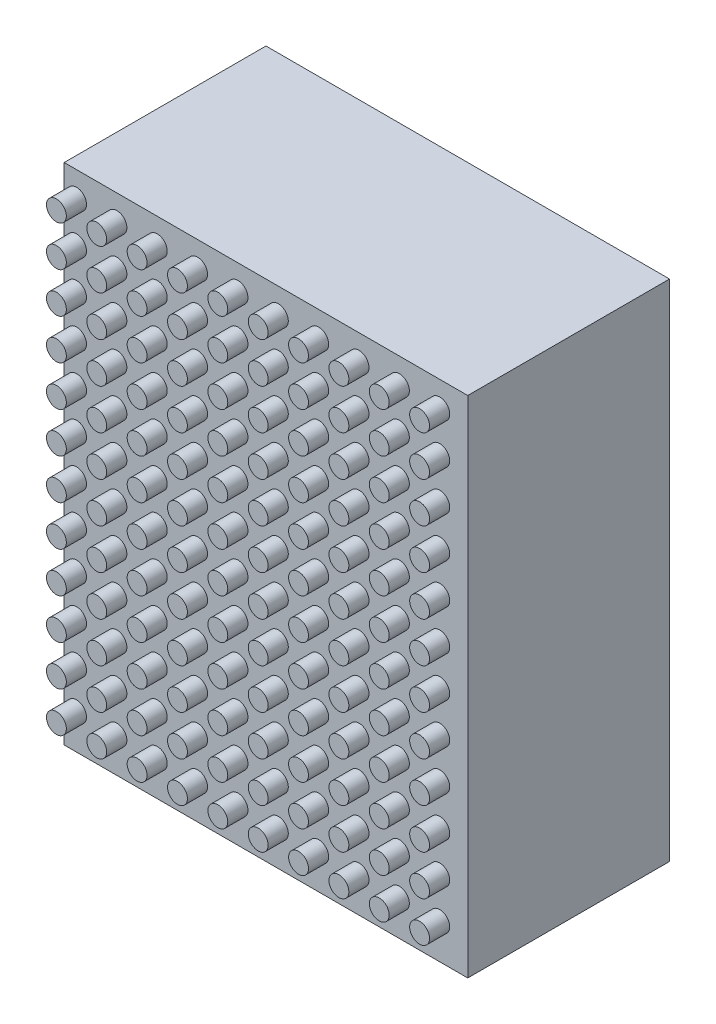
SolidWorks part; units mm, degrees
ref_plane "Front Plane" through (0, 0, 0) normal (0, 0, 1) x (1, 0, 0)
ref_plane "Top Plane" through (0, 0, 0) normal (0, 1, 0) x (1, 0, 0)
ref_plane "Right Plane" through (0, 0, 0) normal (1, 0, 0) x (0, 0, -1)
sketch "Sketch1" plane through (0, 0, 0) normal (0, 0, 1) x (1, 0, 0)
  line L1 (20, -25) -> (-20, -25)
  line L2 (20, -25) -> (20, 25)
  line L3 (20, 25) -> (-20, 25)
  line L4 (-20, -25) -> (-20, 25)
  line L5 (20, -25) -> (-20, 25) construction
  line L6 (20, 25) -> (-20, -25) construction
  point P0 (0, 0)
extrude "Boss-Extrude1" add sketch "Sketch1" along normal blind 20 contours L2 L3 L4 L1
sketch "Sketch2" plane through (0, 0, 20) normal (0, 0, 1) x (1, 0, 0)
  circle A0 centre (17.2286, 22.502) radius 0.9848
extrude "Boss-Extrude2" add sketch "Sketch2" along normal blind 2
pattern_linear "LPattern1" count 10 spacing 4 along (-1, 0, 0) count 12 spacing 4 along (0, -1, 0) of "Boss-Extrude2"
